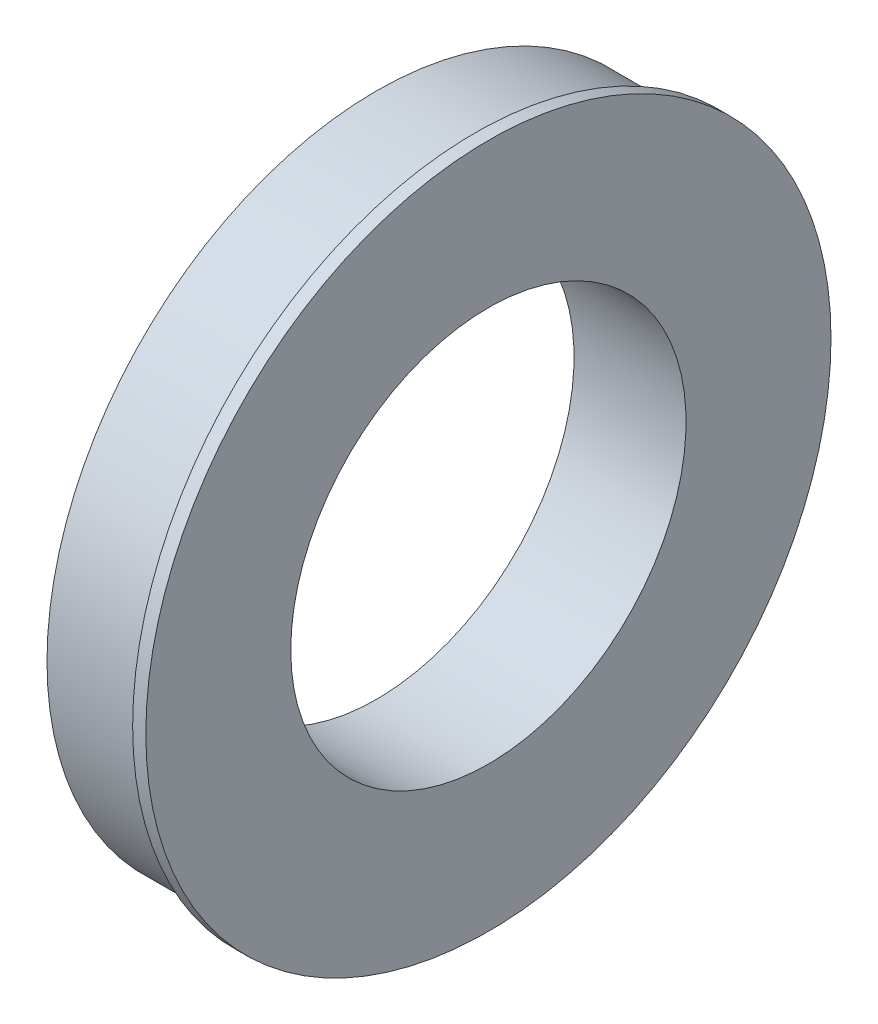
SolidWorks part; units mm, degrees
ref_plane "Front Plane" through (0, 0, 0) normal (0, 0, 1) x (1, 0, 0)
ref_plane "Top Plane" through (0, 0, 0) normal (0, 1, 0) x (1, 0, 0)
ref_plane "Right Plane" through (0, 0, 0) normal (1, 0, 0) x (0, 0, -1)
sketch "Sketch2" plane through (0, 0, 0) normal (1, 0, 0) x (0, 0, -1)
  circle A0 centre (0, 0) radius 38.1
  circle A1 centre (0, 0) radius 63.5
  dimension "D1" = 127
  dimension "D2" = 76.2
extrude "Boss-Extrude1" add sketch "Sketch2" along normal blind 19.05
sketch "Sketch3" plane through (19.05, 0, 0) normal (1, 0, 0) x (0, 0, -1)
  circle A0 centre (0, 0) radius 38.1 construction
  circle A1 centre (0, 0) radius 38.1
  circle A2 centre (0, 0) radius 66.04
  dimension "D1" = 132.08
extrude "Boss-Extrude2" add sketch "Sketch3" along normal blind 2.54
